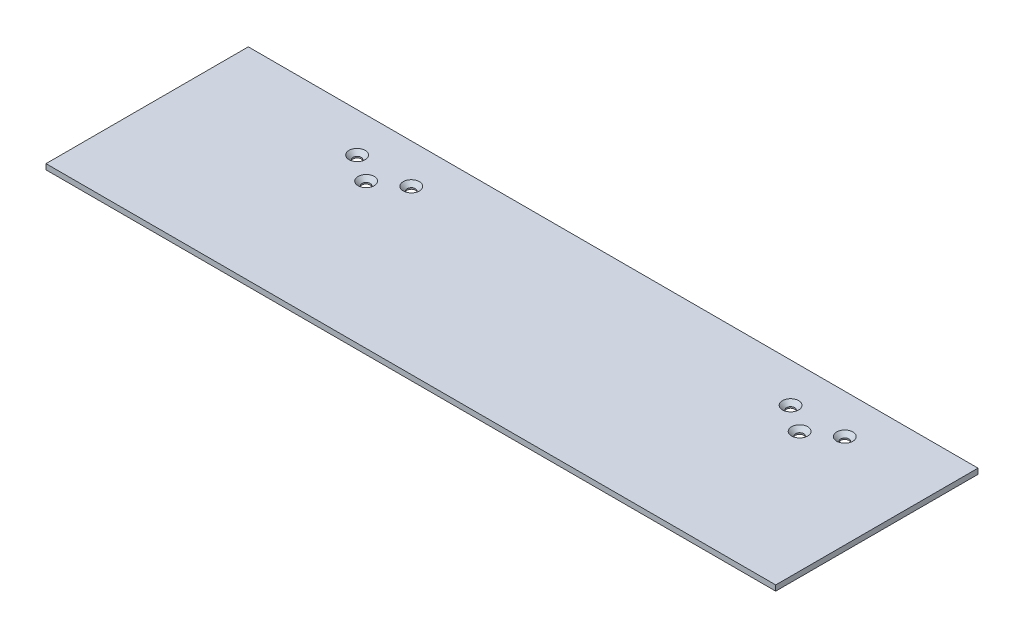
SolidWorks part; units mm, degrees
ref_plane "Front Plane" through (0, 0, 0) normal (0, 0, 1) x (1, 0, 0)
ref_plane "Top Plane" through (0, 0, 0) normal (0, 1, 0) x (1, 0, 0)
ref_plane "Right Plane" through (0, 0, 0) normal (1, 0, 0) x (0, 0, -1)
sketch "Sketch1" plane through (0, 0, 0) normal (0, 1, 0) x (1, 0, 0)
  line L1 (-202, -56) -> (202, -56)
  line L2 (-202, -56) -> (-202, 56)
  line L3 (-202, 56) -> (202, 56)
  line L4 (202, -56) -> (202, 56)
  line L5 (-202, -56) -> (202, 56) construction
  line L6 (-202, 56) -> (202, -56) construction
  point P0 (0, 0)
  dimension "D1" = 404
  dimension "D2" = 112
extrude "Boss-Extrude1" add sketch "Sketch1" along normal blind 3
hole_wizard "CSK for M4 SFHCS1" positions "Sketch2" profile "Sketch3" countersink size "M4" standard "ANSI Metric" end condition through all
sketch "Sketch2" plane through (0, 3, 0) normal (0, 1, 0) x (1, 0, 0)
  line L0 (120, 34.25) -> (150, 34.25)
  line L2 (202, 56) -> (-202, 56) construction
  line L3 (202, -56) -> (202, 56) construction
  point P1 (120, 34.25)
  point P2 (150, 34.25)
  point P14 (135, 24.25)
  point P16 (0, 0)
  point P17 (135, 34.25)
  dimension "D1" = 21.75
  dimension "D2" = 30
  dimension "D3" = 52
  dimension "D4" = 10
sketch "Sketch3" plane through (120, 3, -34.25) normal (1, 0, 0) x (0, 0, 1)
  line L0 (0, 0) -> (0, 3)
  line L1 (0, 3) -> (2.25, 3)
  line L2 (2.25, 3) -> (2.25, 2.23)
  line L3 (2.25, 2.23) -> (4.48, 0)
  line L5 (4.48, 0) -> (0, 0)
  line L6 (-2.25, 2.23) -> (-4.48, 0) construction
  line L11 (0, -6.35) -> (0, 107.95) construction
  dimension "Thru Hole Dia." = 4.5
  dimension "Thru Hole Depth" = 3
  dimension "Near C'Sink Dia." = 8.96
  dimension "Near C'Sink Angle" = 90
pattern_linear "LPattern1" count 2 spacing 240 along (-1, 0, 0) of "CSK for M4 SFHCS1"
